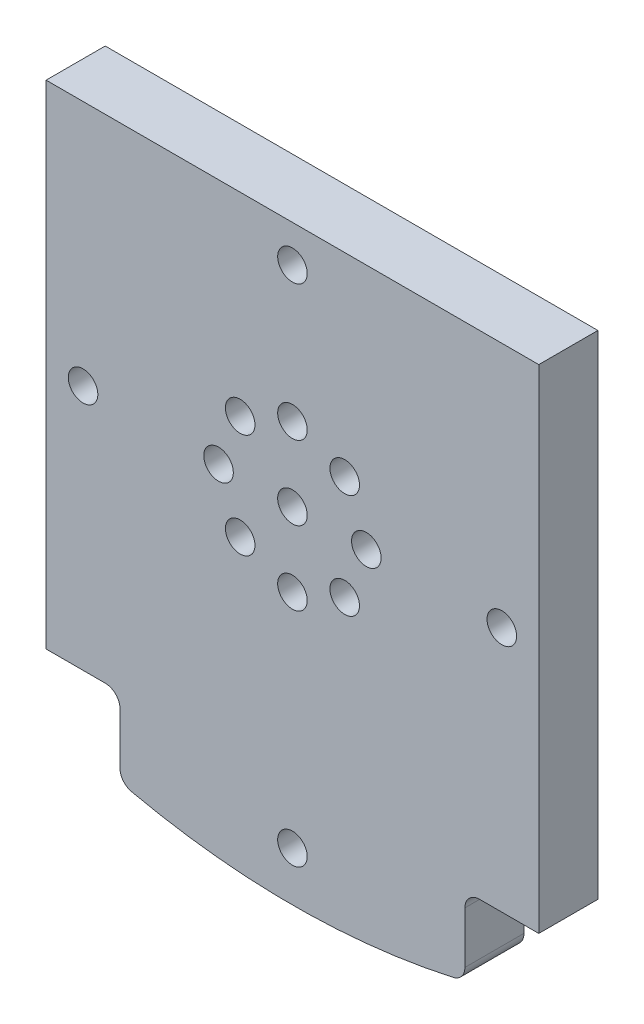
SolidWorks part; units mm, degrees
ref_plane "前视基准面" through (0, 0, 0) normal (0, 0, 1) x (1, 0, 0)
ref_plane "上视基准面" through (0, 0, 0) normal (0, 1, 0) x (1, 0, 0)
ref_plane "右视基准面" through (0, 0, 0) normal (1, 0, 0) x (0, 0, -1)
sketch "草图1" plane through (0, 0, 0) normal (0, 0, 1) x (1, 0, 0)
  line L0 (-35, -53) -> (-35, -63.4747)
  line L3 (50, -50) -> (38, -50)
  line L4 (50, -50) -> (50, 50)
  line L5 (50, 50) -> (0, 50)
  line L6 (-50, -50) -> (-50, 50)
  line L7 (50, -50) -> (-50, 50) construction
  line L8 (50, 50) -> (-50, -50) construction
  line L9 (35, -53) -> (35, -63.4747)
  line L10 (0, 0) -> (0, 50) construction
  line L11 (0, 50) -> (-50, 50)
  line L12 (-38, -50) -> (-50, -50)
  line L13 (35, -50) -> (-35, -50) construction
  line L14 (0, 0) -> (15, 0) construction
  arc A1 (-32.6531, -66.4028) -> (32.6531, -66.4028) centre (0, 80) ccw
  arc A2 (35, -65.8595) -> (-35, -65.8595) centre (0, 80) ccw construction
  arc A3 (50, 50) -> (-50, 50) centre (0, 50) ccw construction
  arc A4 (-50, 50) -> (0, 0) centre (0, 50) ccw construction
  arc A5 (0, 0) -> (50, 50) centre (0, 50) ccw construction
  arc A7 (38, -50) -> (35, -53) centre (38, -53) ccw
  arc A8 (35, -63.4747) -> (32.6531, -66.4028) centre (32, -63.4747) cw
  arc A9 (-32.6531, -66.4028) -> (-35, -63.4747) centre (-32, -63.4747) cw
  arc A10 (-35, -53) -> (-38, -50) centre (-38, -53) ccw
  circle A12 centre (0, 0) radius 42.5 construction
  circle A13 centre (-42.5, 0) radius 3
  circle A14 centre (42.5, 0) radius 3
  circle A15 centre (0, 0) radius 60 construction
  circle A16 centre (0, -60) radius 3
  circle A17 centre (0, 0) radius 3
  circle A18 centre (0, 42.5) radius 3
  circle A19 centre (15, 0) radius 3
  circle A20 centre (10.6066, -10.6066) radius 3
  circle A21 centre (0, -15) radius 3
  circle A22 centre (-10.6066, -10.6066) radius 3
  circle A23 centre (-15, 0) radius 3
  circle A24 centre (-10.6066, 10.6066) radius 3
  circle A25 centre (0, 15) radius 3
  circle A26 centre (10.6066, 10.6066) radius 3
  point P0 (0, 0)
  point P14 (0, -50)
  point P16 (0, -70)
  dimension "D2" = 6
  dimension "D3" = 300
  dimension "D7" = 85
  dimension "D8" = 6
  dimension "D9" = 6
  dimension "D10" = 6
  dimension "D11" = 120
  dimension "D12" = 6
  dimension "D13" = 6
  dimension "D1" = 100
  dimension "D4" = 15
  dimension "D5" = 15
  dimension "D6" = 20
  dimension "D14" = 80
  dimension "D15" = 15
  dimension "D17" = 15
  dimension "D16" = 8
extrude "凸台-拉伸1" add sketch "草图1" along normal blind 12
sketch "草图3" plane through (0, 0, 0) normal (0, 0, -1) x (-1, 0, 0)
  circle A2 centre (0, -60) radius 5.5
  circle A3 centre (0, -60) radius 5.5
  dimension "D1" = 2.5
extrude "切除-拉伸2" cut sketch "草图3" against normal blind 6
